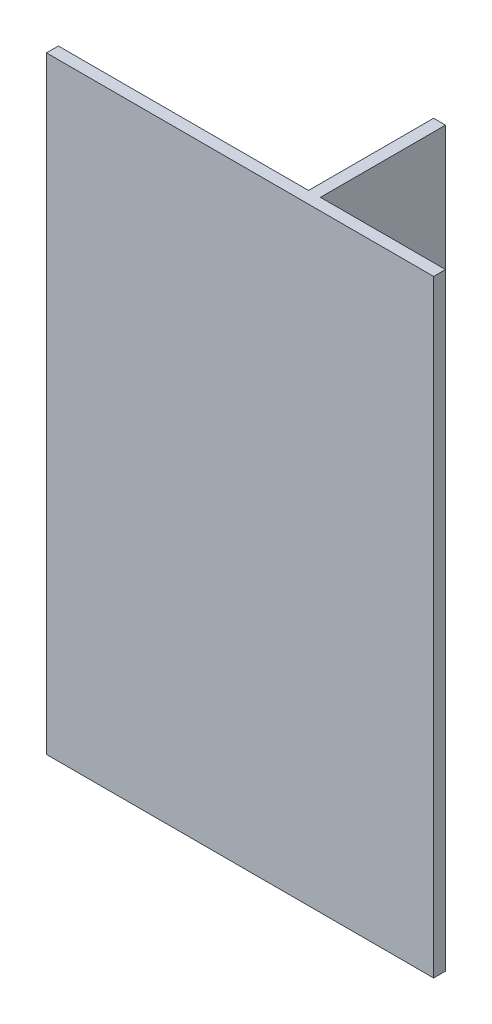
SolidWorks part; units mm, degrees
ref_plane "Front Plane" through (0, 0, 0) normal (0, 0, 1) x (1, 0, 0)
ref_plane "Top Plane" through (0, 0, 0) normal (0, 1, 0) x (1, 0, 0)
ref_plane "Right Plane" through (0, 0, 0) normal (1, 0, 0) x (0, 0, -1)
sketch "Sketch1" plane through (0, 0, 0) normal (0, 1, 0) x (1, 0, 0)
  line L0 (44, 2) -> (65, 2)
  line L1 (0, 0) -> (65, 0)
  line L2 (0, 0) -> (0, 2)
  line L3 (0, 2) -> (42, 2)
  line L4 (65, 0) -> (65, 2)
  line L6 (42, 2) -> (42, 23)
  line L7 (42, 23) -> (44, 23)
  line L8 (44, 2) -> (44, 23)
  dimension "D1" = 65
  dimension "D2" = 2
  dimension "D3" = 21
  dimension "D4" = 21
extrude "Boss-Extrude1" add sketch "Sketch1" along normal blind 102 contours L6 L7 L8 L0 L4 L1 L2 L3
